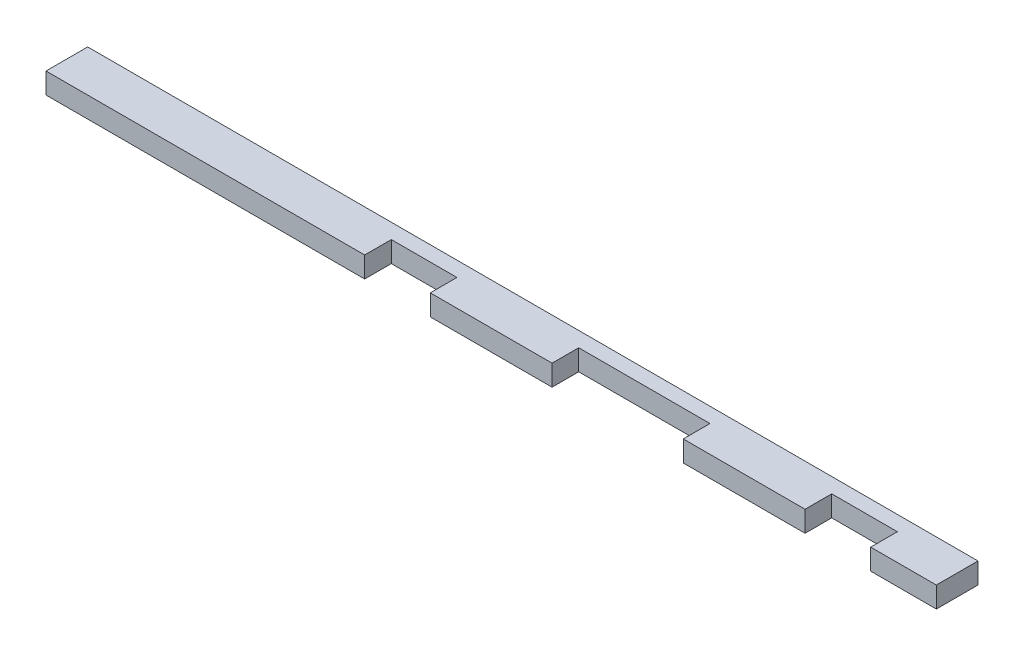
SolidWorks part; units mm, degrees
ref_plane "Front Plane" through (0, 0, 0) normal (0, 0, 1) x (1, 0, 0)
ref_plane "Top Plane" through (0, 0, 0) normal (0, 1, 0) x (1, 0, 0)
ref_plane "Right Plane" through (0, 0, 0) normal (1, 0, 0) x (0, 0, -1)
sketch "Sketch1" plane through (0, 0, 0) normal (0, 1, 0) x (1, 0, 0)
  line L0 (0, 0) -> (24.2756, 0)
  line L1 (0, 3.175) -> (67.8269, 3.175)
  line L2 (10, 2.032) -> (10, 0) construction
  line L3 (0, 2.032) -> (67.8269, 2.032) construction
  line L4 (0, 3.175) -> (0, 0)
  line L5 (67.8269, 3.175) -> (67.8269, 0)
  line L6 (57.8269, 2.032) -> (57.8269, 0)
  line L7 (19.2756, 2.032) -> (19.2756, 0) construction
  line L8 (48.5513, 2.032) -> (48.5513, 0)
  line L9 (29.2756, 2.032) -> (29.2756, 0)
  line L10 (38.5513, 2.032) -> (38.5513, 0)
  line L11 (24.2756, 2.032) -> (24.2756, 0)
  line L12 (29.2756, 0) -> (38.5513, 0)
  line L13 (48.5513, 0) -> (57.8269, 0)
  line L14 (62.8269, 0) -> (62.8269, 2.032)
  line L15 (62.8269, 0) -> (67.8269, 0)
  line L16 (24.2756, 2.032) -> (29.2756, 2.032)
  line L17 (38.5513, 2.032) -> (48.5513, 2.032)
  line L18 (57.8269, 2.032) -> (62.8269, 2.032)
  dimension "D1" = 67.8269
  dimension "D2" = 10
  dimension "D3" = 2.032
  dimension "D4" = 1.143
  dimension "D5" = 10
  dimension "D6" = 5
  dimension "D7" = 9.2756
  dimension "D8" = 9.2756
  dimension "D9" = 10
  dimension "D10" = 10
  dimension "D11" = 9.2756
  dimension "D12" = 5
extrude "Boss-Extrude1" add sketch "Sketch1" along normal blind 1.5875
